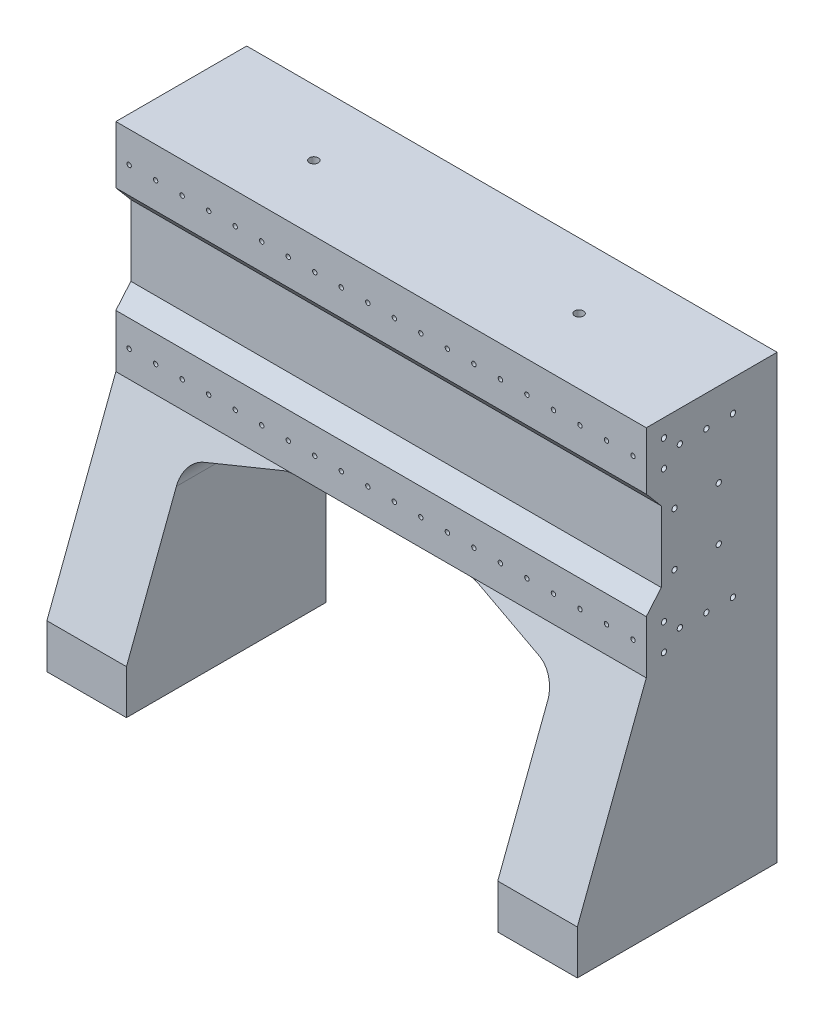
SolidWorks part; units mm, degrees
ref_plane "Front Plane" through (0, 0, 0) normal (0, 0, 1) x (1, 0, 0)
ref_plane "Top Plane" through (0, 0, 0) normal (0, 1, 0) x (1, 0, 0)
ref_plane "Right Plane" through (0, 0, 0) normal (1, 0, 0) x (0, 0, -1)
sketch "Sketch1" plane through (0, 0, 0) normal (0, 0, 1) x (1, 0, 0)
  line L1 (-300, 250) -> (300, 250)
  line L2 (-300, 250) -> (-300, -250)
  line L3 (-300, -250) -> (300, -250)
  line L4 (300, 250) -> (300, -250)
  line L5 (0, -250) -> (0, 250) construction
  line L6 (-300, 0) -> (300, 0) construction
  point P0 (0, 0)
  dimension "D1" = 500
  dimension "D2" = 600
extrude "Boss-Extrude1" add sketch "Sketch1" along normal blind 226
sketch "Sketch2" plane through (0, 0, 226) normal (0, 0, 1) x (1, 0, 0)
  line L1 (-210, -225) -> (-210, -30)
  line L8 (-210, -30) -> (210, -30)
  line L9 (210, -250) -> (-210, -250)
  line L15 (210, -30) -> (210, -225)
  line L16 (-210, -225) -> (-210, -250)
  line L17 (210, -225) -> (210, -250)
extrude "Cut-Extrude1" cut sketch "Sketch2" along direction (0, 0, 1) on the side against the normal through all flip side to cut
sketch "Sketch22" plane through (0, 0, 226) normal (0, 0, 1) x (1, 0, 0)
  line L0 (-210, -30) -> (210, -30) construction
  line L1 (-210, -30) -> (210, -30)
  line L5 (0, 5) -> (105, 5)
  line L6 (0, 5) -> (-105, 5)
  line L7 (-105, 5) -> (-210, -30)
  line L8 (105, 5) -> (210, -30)
extrude "Cut-Extrude8" cut sketch "Sketch22" against normal through all
sketch "Sketch4" plane through (-300, 0, 0) normal (-1, 0, 0) x (0, 0, 1)
  line L0 (148, 25) -> (148, 5)
  line L6 (148, 250) -> (148, 25)
  line L7 (148, 250) -> (226, 250)
  line L8 (226, 250) -> (226, -250) construction
  line L10 (226, 250) -> (226, -145)
  line L17 (226, -145) -> (226, -165)
  line L19 (226, -165) -> (226, -200)
  line L20 (226, -200) -> (148, 5)
extrude "Cut-Extrude2" cut sketch "Sketch4" against normal through all
sketch "Sketch5" plane through (-300, 0, 0) normal (-1, 0, 0) x (0, 0, 1)
  line L0 (131, 160) -> (131, 165)
  line L1 (148, 250) -> (148, 5) construction
  line L3 (131, 90) -> (131, 85)
  line L5 (148, 65) -> (148, 185)
  line L6 (131, 165) -> (148, 185)
  line L7 (131, 125) -> (131, 90)
  line L9 (131, 125) -> (131, 160)
  line L12 (131, 85) -> (148, 65)
extrude "Cut-Extrude3" cut sketch "Sketch5" against normal through all
sketch "Sketch7" plane through (0, 0, 148) normal (0, 0, 1) x (1, 0, 0)
  line L0 (-285, 197.5) -> (-285, 200)
  line L2 (-285, 32.5) -> (-285, 30)
  circle A0 centre (-285, 215) radius 2.5
  circle A1 centre (-255, 215) radius 2.5
  circle A2 centre (-225, 215) radius 2.5
  circle A3 centre (-195, 215) radius 2.5
  circle A4 centre (-165, 215) radius 2.5
  circle A5 centre (-135, 215) radius 2.5
  circle A6 centre (-105, 215) radius 2.5
  circle A7 centre (-75, 215) radius 2.5
  circle A8 centre (-45, 215) radius 2.5
  circle A9 centre (-15, 215) radius 2.5
  circle A10 centre (15, 215) radius 2.5
  circle A11 centre (45, 215) radius 2.5
  circle A12 centre (75, 215) radius 2.5
  circle A13 centre (105, 215) radius 2.5
  circle A14 centre (135, 215) radius 2.5
  circle A15 centre (165, 215) radius 2.5
  circle A16 centre (195, 215) radius 2.5
  circle A17 centre (225, 215) radius 2.5
  circle A18 centre (255, 215) radius 2.5
  circle A19 centre (285, 215) radius 2.5
  circle A21 centre (-255, 35) radius 2.5
  circle A22 centre (-225, 35) radius 2.5
  circle A23 centre (-195, 35) radius 2.5
  circle A24 centre (-165, 35) radius 2.5
  circle A25 centre (-135, 35) radius 2.5
  circle A26 centre (-105, 35) radius 2.5
  circle A27 centre (-75, 35) radius 2.5
  circle A28 centre (-45, 35) radius 2.5
  circle A29 centre (-15, 35) radius 2.5
  circle A30 centre (15, 35) radius 2.5
  circle A31 centre (45, 35) radius 2.5
  circle A32 centre (75, 35) radius 2.5
  circle A33 centre (105, 35) radius 2.5
  circle A34 centre (135, 35) radius 2.5
  circle A35 centre (165, 35) radius 2.5
  circle A36 centre (195, 35) radius 2.5
  circle A37 centre (225, 35) radius 2.5
  circle A38 centre (255, 35) radius 2.5
  circle A39 centre (285, 35) radius 2.5
  circle A41 centre (-285, 35) radius 2.5
  circle A42 centre (315, 35) radius 2.5 [skipped]
  circle A43 centre (315, 215) radius 2.5 [skipped]
  dimension "D1" = 21
  dimension "D2" = 2
extrude "Cut-Extrude5" cut sketch "Sketch7" against normal blind 25 contours A41 | A21 | A22 | A23 | A24 | A25 | A26 | A27 | A28 | A29 | A30 | A31 | A32 | A33 | A34 | A35 | A36 | A37 | A38 | A39 | A19 | A18 | A17 | A16 | A15 | A14 | A13 | A12 | A11 | A10 | A9 | A8 | A7 | A6 | A5 | A4 | A3 | A2 | A1 | A0
sketch "Sketch8" plane through (0, -250, 0) normal (0, -1, 0) x (1, 0, 0)
  circle A0 centre (240, 171) radius 10 construction
  circle A1 centre (275, 171) radius 10 construction
  circle A4 centre (240, 51) radius 10 construction
  circle A5 centre (275, 51) radius 10 construction
  circle A6 centre (-275, 51) radius 10 construction
  circle A7 centre (-240, 51) radius 10 construction
  circle A10 centre (-275, 171) radius 10 construction
  circle A11 centre (-240, 171) radius 10 construction
  circle A12 centre (240, 171) radius 10
  circle A13 centre (275, 171) radius 10
  circle A16 centre (240, 51) radius 10
  circle A17 centre (275, 51) radius 10
  circle A18 centre (-275, 51) radius 10
  circle A19 centre (-240, 51) radius 10
  circle A22 centre (-275, 171) radius 10
  circle A23 centre (-240, 171) radius 10
extrude "Cut-Extrude6" cut sketch "Sketch8" against normal blind 35
sketch "Sketch10" plane through (0, 0, 0) normal (0, 0, -1) x (-1, 0, 0)
  line L1 (150, 142) -> (150, 138)
  line L2 (150, 138) -> (235, 138)
  line L11 (300, 250) -> (300, 155)
  line L12 (300, 250) -> (300, -250) construction
  line L13 (300, 155) -> (235, 155)
  line L14 (150, 155) -> (150, 250)
  line L15 (-300, 250) -> (300, 250) construction
  line L16 (150, 250) -> (300, 250)
  line L17 (150, 155) -> (150, 142)
  line L19 (235, 142) -> (235, 155)
  line L20 (235, 138) -> (235, 142)
sketch "Sketch11" plane through (-300, 0, 0) normal (-1, 0, 0) x (0, 0, 1)
  line L2 (148, 17.5) -> (148, 22.5)
  line L3 (148, 227.5) -> (148, 232.5)
  line L6 (148, 200) -> (128, 200)
  line L7 (148, 227.5) -> (148, 230)
  line L11 (148, 230) -> (128, 230)
  line L12 (148, 20) -> (148, 22.5)
  line L14 (148, 50) -> (128, 50)
  line L15 (148, 22.5) -> (148, 20)
  line L16 (148, 20) -> (128, 20)
  circle A0 centre (116, 155) radius 3
  circle A1 centre (116, 95) radius 3
  circle A2 centre (66, 95) radius 3
  circle A3 centre (66, 155) radius 3
hole_wizard "Ø6.0mm Dowel Hole1" positions "Sketch12" profile "Sketch13" hole size "Ø6.0" standard "ANSI Metric"
sketch "Sketch12" plane through (-300, 0, 0) normal (-1, 0, 0) x (0, 0, 1)
  point P6 (116, 95)
  point P9 (66, 95)
  point P12 (66, 155)
  point P15 (116, 155)
  point P29 (128, 230)
  point P32 (128, 200)
  point P35 (128, 50)
  point P38 (128, 20)
sketch "Sketch13" plane through (-300, 95, 116) normal (0, 1, 0) x (0, 0, 1)
  line L0 (0, 0) -> (0, 30)
  line L1 (0, 30) -> (3, 28.1974)
  line L2 (3, 28.1974) -> (3, 0)
  line L5 (3, 0) -> (0, 0)
  line L10 (0, 30) -> (-3, 28.1974) construction
  line L11 (0, -6.35) -> (0, 107.95) construction
  dimension "Hole Dia." = 6
  dimension "Hole Depth" = 30
  dimension "Drill Angle" = 118
sketch "Sketch16" plane through (300, 0, 0) normal (1, 0, 0) x (0, 0, -1)
  line L0 (-148, 20) -> (-128, 20) construction
  line L1 (-148, 50) -> (-128, 50) construction
  line L2 (-148, 200) -> (-128, 200) construction
  line L3 (-148, 230) -> (-128, 230) construction
  line L4 (-148, 20) -> (-128, 20)
  line L5 (-148, 50) -> (-128, 50)
  line L6 (-148, 200) -> (-128, 200)
  line L7 (-148, 230) -> (-128, 230)
  circle A8 centre (-116, 95) radius 3 construction
  circle A9 centre (-66, 95) radius 3 construction
  circle A10 centre (-66, 155) radius 3 construction
  circle A11 centre (-116, 155) radius 3 construction
  circle A12 centre (-116, 95) radius 3
  circle A13 centre (-66, 95) radius 3
  circle A14 centre (-66, 155) radius 3
  circle A15 centre (-116, 155) radius 3
hole_wizard "Ø6.0mm Dowel Hole2" positions "Sketch17" profile "Sketch18" hole size "Ø6.0" standard "ANSI Metric"
sketch "Sketch17" plane through (300, 0, 0) normal (1, 0, 0) x (0, 0, -1)
  point P25 (-128, 230)
  point P28 (-128, 200)
  point P31 (-116, 155)
  point P34 (-66, 155)
  point P37 (-66, 95)
  point P40 (-116, 95)
  point P43 (-128, 50)
  point P46 (-128, 20)
sketch "Sketch18" plane through (300, 230, 128) normal (0, 1, 0) x (0, 0, -1)
  line L0 (0, 0) -> (0, 30)
  line L1 (0, 30) -> (3, 28.1974)
  line L2 (3, 28.1974) -> (3, 0)
  line L5 (3, 0) -> (0, 0)
  line L10 (0, 30) -> (-3, 28.1974) construction
  line L11 (0, -6.35) -> (0, 107.95) construction
  dimension "Hole Dia." = 6
  dimension "Hole Depth" = 30
  dimension "Drill Angle" = 118
sketch "Sketch19" plane through (300, 0, 0) normal (1, 0, 0) x (0, 0, -1)
  line L0 (-148, 37.5) -> (-148, 32.5) construction
  line L1 (-148, 217.5) -> (-148, 212.5) construction
  line L2 (-148, 37.5) -> (-148, 32.5)
  line L3 (-148, 217.5) -> (-148, 212.5)
  line L4 (-140, 35) -> (-110, 35)
  line L5 (-110, 35) -> (-80, 35)
  line L6 (-80, 35) -> (-50, 35)
  line L7 (-140, 215) -> (-110, 215)
  line L8 (-110, 215) -> (-80, 215)
  line L9 (-80, 215) -> (-50, 215)
  line L10 (-148, 217.5) -> (-148, 215)
hole_wizard "Ø6.0mm Dowel Hole3" positions "Sketch20" profile "Sketch21" hole size "Ø6.0" standard "ANSI Metric"
sketch "Sketch20" plane through (300, 0, 0) normal (1, 0, 0) x (0, 0, -1)
  point P0 (-110, 215)
  point P3 (-80, 215)
  point P6 (-50, 215)
  point P9 (-50, 35)
  point P12 (-80, 35)
  point P15 (-110, 35)
sketch "Sketch21" plane through (300, 215, 110) normal (0, 1, 0) x (0, 0, -1)
  line L0 (0, 0) -> (0, 30)
  line L1 (0, 30) -> (3, 28.1974)
  line L2 (3, 28.1974) -> (3, 0)
  line L5 (3, 0) -> (0, 0)
  line L10 (0, 30) -> (-3, 28.1974) construction
  line L11 (0, -6.35) -> (0, 107.95) construction
  dimension "Hole Dia." = 6
  dimension "Hole Depth" = 30
  dimension "Drill Angle" = 118
fillet "Fillet2" radius 30 4 edges at (210, -30, 80.6585) (-210, -30, 80.6585) (-105, 5, 74) (105, 5, 74)
sketch "Sketch23" plane through (-300, 0, 0) normal (-1, 0, 0) x (0, 0, 1)
  circle A0 centre (110, 35) radius 3 construction
  circle A1 centre (80, 35) radius 3 construction
  circle A2 centre (50, 35) radius 3 construction
  circle A3 centre (110, 215) radius 3 construction
  circle A4 centre (80, 215) radius 3 construction
  circle A5 centre (50, 215) radius 3 construction
  circle A6 centre (110, 35) radius 3
  circle A7 centre (80, 35) radius 3
  circle A8 centre (50, 35) radius 3
  circle A9 centre (110, 215) radius 3
  circle A10 centre (80, 215) radius 3
  circle A11 centre (50, 215) radius 3
hole_wizard "Ø6.0mm Dowel Hole4" positions "Sketch24" profile "Sketch25" hole size "Ø6.0" standard "ANSI Metric"
sketch "Sketch24" plane through (-300, 0, 0) normal (-1, 0, 0) x (0, 0, 1)
  point P0 (110, 215)
  point P3 (80, 215)
  point P6 (50, 215)
  point P9 (110, 35)
  point P12 (80, 35)
  point P15 (50, 35)
sketch "Sketch25" plane through (-300, 215, 110) normal (0, 1, 0) x (0, 0, 1)
  line L0 (0, 0) -> (0, 29.8026)
  line L1 (0, 29.8026) -> (3, 28)
  line L2 (3, 28) -> (3, 0)
  line L5 (3, 0) -> (0, 0)
  line L10 (0, 29.8026) -> (-3, 28) construction
  line L11 (0, -6.35) -> (0, 107.95) construction
  dimension "Hole Dia." = 6
  dimension "Hole Depth" = 28
  dimension "Drill Angle" = 118
sketch "Sketch26" plane through (0, 250, 0) normal (0, 1, 0) x (1, 0, 0)
  line L0 (-300, 0) -> (-300, -148)
  line L1 (-300, -74) -> (-150, -74)
  line L2 (300, 0) -> (300, -148)
  line L3 (300, -74) -> (150, -74)
hole_wizard "Ø10.0mm Dowel Hole1" positions "Sketch27" profile "Sketch28" hole size "Ø10.0" standard "ANSI Metric"
sketch "Sketch27" plane through (0, 250, 0) normal (0, 1, 0) x (1, 0, 0)
  point P0 (-150, -74)
  point P3 (150, -74)
sketch "Sketch28" plane through (-150, 250, 74) normal (1, 0, 0) x (0, 0, 1)
  line L0 (0, 0) -> (0, 31.0043)
  line L1 (0, 31.0043) -> (5, 28)
  line L2 (5, 28) -> (5, 0)
  line L5 (5, 0) -> (0, 0)
  line L10 (0, 31.0043) -> (-5, 28) construction
  line L11 (0, -6.35) -> (0, 107.95) construction
  dimension "Hole Dia." = 10
  dimension "Hole Depth" = 28
  dimension "Drill Angle" = 118
